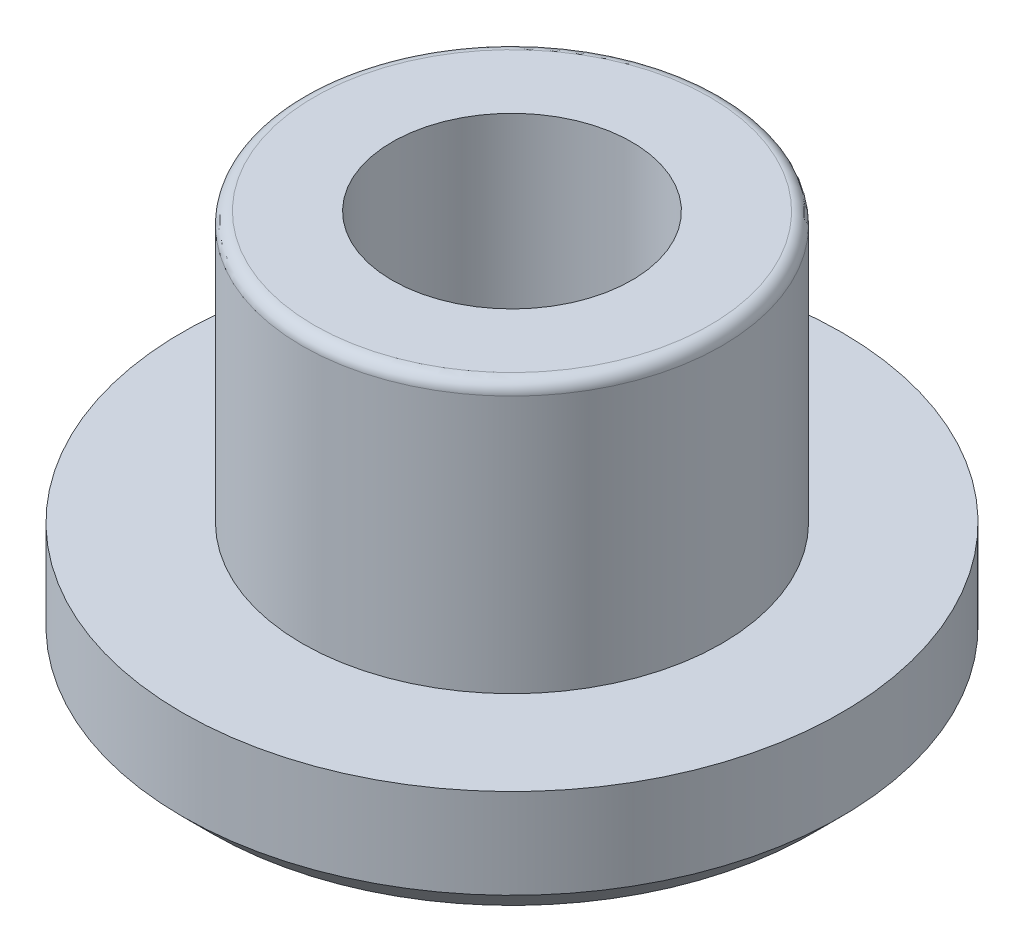
SolidWorks part; units mm, degrees
ref_plane "前视基准面" through (0, 0, 0) normal (0, 0, 1) x (1, 0, 0)
ref_plane "上视基准面" through (0, 0, 0) normal (0, 1, 0) x (1, 0, 0)
ref_plane "右视基准面" through (0, 0, 0) normal (1, 0, 0) x (0, 0, -1)
sketch "草图1" plane through (0, 0, 0) normal (0, 1, 0) x (1, 0, 0)
  circle A0 centre (0, 0) radius 5.5
  dimension "D1" = 11
extrude "凸台-拉伸1" add sketch "草图1" along normal blind 2
sketch "草图2" plane through (0, 2, 0) normal (0, 1, 0) x (1, 0, 0)
  circle A0 centre (0, 0) radius 3.5
  dimension "D1" = 7
extrude "凸台-拉伸2" add sketch "草图2" along normal blind 4.5
sketch "草图3" plane through (0, 6.5, 0) normal (0, 1, 0) x (1, 0, 0)
  circle A0 centre (0, 0) radius 2
  dimension "D1" = 4
extrude "切除-拉伸1" cut sketch "草图3" against normal blind 5
chamfer "倒角1" distance 0.5 angle 45 1 edges at (0, 0, 5.5)
fillet "圆角1" radius 0.2 1 edges at (0, 6.5, 3.5)
